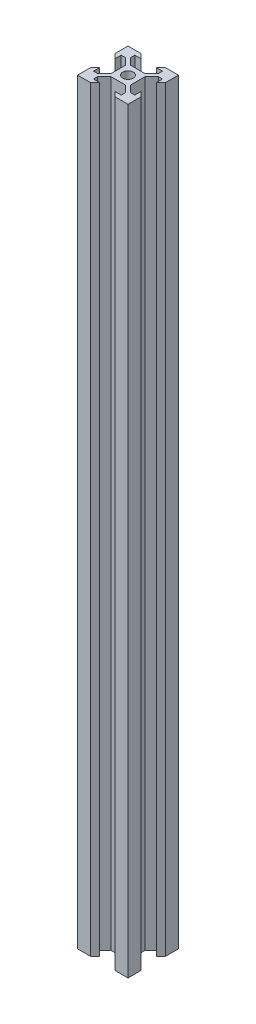
SolidWorks part; units mm, degrees
ref_plane "Front Plane" through (0, 0, 0) normal (0, 0, 1) x (1, 0, 0)
ref_plane "Top Plane" through (0, 0, 0) normal (0, 1, 0) x (1, 0, 0)
ref_plane "Right Plane" through (0, 0, 0) normal (1, 0, 0) x (0, 0, -1)
sketch "Sketch1" plane through (0, 0, 0) normal (0, 1, 0) x (1, 0, 0)
  line L0 (3.9007, 2.84) -> (2.84, 3.9007) construction
  line L1 (-10, -10) -> (10, -10) construction
  line L2 (-10, -10) -> (-10, 10) construction
  line L3 (-10, 10) -> (10, 10) construction
  line L4 (10, -10) -> (10, 10) construction
  line L5 (-10, -10) -> (10, 10) construction
  line L6 (-10, 10) -> (10, -10) construction
  line L7 (-2.84, -2.84) -> (2.84, -2.84) construction
  line L8 (-2.84, -2.84) -> (-2.84, 2.84) construction
  line L9 (-2.84, 2.84) -> (2.84, 2.84) construction
  line L10 (2.84, -2.84) -> (2.84, 2.84) construction
  line L11 (-2.84, -2.84) -> (2.84, 2.84) construction
  line L12 (-2.84, 2.84) -> (2.84, -2.84) construction
  line L13 (2.84, -3.9007) -> (3.9007, -2.84) construction
  line L14 (-3.9007, -2.84) -> (-2.84, -3.9007) construction
  line L15 (-2.84, 3.9007) -> (-3.9007, 2.84) construction
  line L16 (-3.1, 10) -> (3.1, 10) construction
  line L17 (-3.1, 10) -> (-3.1, 8.2) construction
  line L18 (-3.1, 8.2) -> (-4.9, 10)
  line L19 (3.1, 8.2) -> (3.1, 10) construction
  line L20 (-3.1, 8.2) -> (-8.2, 8.2) construction
  line L21 (-2.84, 3.9007) -> (-7.1393, 8.2) construction
  line L22 (-5.4993, 8.2) -> (-5.4993, 6.56)
  line L23 (-4.9, 10) -> (-10, 10)
  line L24 (-3.9007, -3.9007) -> (3.9007, -3.9007) construction
  line L25 (-3.9007, -3.9007) -> (-3.9007, 3.9007) construction
  line L26 (-3.9007, 3.9007) -> (3.9007, 3.9007) construction
  line L27 (3.9007, -3.9007) -> (3.9007, 3.9007) construction
  line L28 (-3.9007, -3.9007) -> (3.9007, 3.9007) construction
  line L29 (-3.9007, 3.9007) -> (3.9007, -3.9007) construction
  line L30 (-5.4993, 6.56) -> (-2.84, 3.9007)
  line L31 (-2.84, 3.9007) -> (0, 3.9007)
  line L32 (-5.4993, 8.2) -> (-3.1, 8.2)
  line L33 (-3.9007, 2.84) -> (-3.9007, 0)
  line L34 (-6.56, 5.4993) -> (-3.9007, 2.84)
  line L35 (-8.2, 5.4993) -> (-6.56, 5.4993)
  line L36 (-8.2, 5.4993) -> (-8.2, 3.1)
  line L37 (-8.2, 3.1) -> (-10, 4.9)
  line L38 (-10, 4.9) -> (-10, 10)
  line L39 (2.84, 3.9007) -> (0, 3.9007)
  line L40 (5.4993, 6.56) -> (2.84, 3.9007)
  line L41 (5.4993, 8.2) -> (5.4993, 6.56)
  line L42 (5.4993, 8.2) -> (3.1, 8.2)
  line L43 (3.1, 8.2) -> (4.9, 10)
  line L44 (4.9, 10) -> (10, 10)
  line L45 (10, 4.9) -> (10, 10)
  line L46 (8.2, 3.1) -> (10, 4.9)
  line L47 (8.2, 5.4993) -> (8.2, 3.1)
  line L48 (8.2, 5.4993) -> (6.56, 5.4993)
  line L49 (6.56, 5.4993) -> (3.9007, 2.84)
  line L50 (3.9007, 2.84) -> (3.9007, 0)
  line L51 (3.9007, -2.84) -> (3.9007, 0)
  line L52 (6.56, -5.4993) -> (3.9007, -2.84)
  line L53 (8.2, -5.4993) -> (6.56, -5.4993)
  line L54 (8.2, -5.4993) -> (8.2, -3.1)
  line L55 (8.2, -3.1) -> (10, -4.9)
  line L56 (10, -4.9) -> (10, -10)
  line L57 (4.9, -10) -> (10, -10)
  line L58 (3.1, -8.2) -> (4.9, -10)
  line L59 (5.4993, -8.2) -> (3.1, -8.2)
  line L60 (5.4993, -8.2) -> (5.4993, -6.56)
  line L61 (5.4993, -6.56) -> (2.84, -3.9007)
  line L62 (2.84, -3.9007) -> (0, -3.9007)
  line L63 (-2.84, -3.9007) -> (0, -3.9007)
  line L64 (-5.4993, -6.56) -> (-2.84, -3.9007)
  line L65 (-5.4993, -8.2) -> (-5.4993, -6.56)
  line L66 (-5.4993, -8.2) -> (-3.1, -8.2)
  line L67 (-3.1, -8.2) -> (-4.9, -10)
  line L68 (-4.9, -10) -> (-10, -10)
  line L69 (-10, -4.9) -> (-10, -10)
  line L70 (-8.2, -3.1) -> (-10, -4.9)
  line L71 (-8.2, -5.4993) -> (-8.2, -3.1)
  line L72 (-8.2, -5.4993) -> (-6.56, -5.4993)
  line L73 (-6.56, -5.4993) -> (-3.9007, -2.84)
  line L74 (-3.9007, -2.84) -> (-3.9007, 0)
  circle A0 centre (0, 0) radius 2.1
  circle A1 centre (0, 0) radius 2.1
  circle A2 centre (0, 0) radius 2.1
  circle A3 centre (0, 0) radius 2.1
  point P0 (0, 0)
  point P15 (3.3703, 3.3703)
  point P27 (0, 0)
  point P28 (0, 10)
  point P87 (0, 0)
  dimension "D2" = 4.2
  dimension "D1" = 20
  dimension "D3" = 5.68
  dimension "D4" = 1.5
  dimension "D6" = 6.2
  dimension "D7" = 1.8
  dimension "D8" = 45
  dimension "D9" = 1.64
  dimension "D10" = 4
  dimension "D11" = 90
  dimension "D12" = 1.64
  dimension "D13" = 20
  dimension "D14" = 1.5
  dimension "D15" = 5.68
  dimension "D16" = 6.2
  dimension "D17" = 1.8
  dimension "D5" = 4
extrude "Boss-Extrude1" add sketch "Sketch1" along normal blind 300 contours L74 L73 L72 L71 L70 L69 L68 L67 L66 L65 L64 L63 L62 L61 L60 L59 L58 L57 L56 L55 L54 L53 L52 L51 L50 L49 L48 L47 L46 L45 L44 L43 L42 L41 L40 L39 L31 L30 L22 L32 L18 L23 L38 L37 L36 L35 L34 L33 A0
